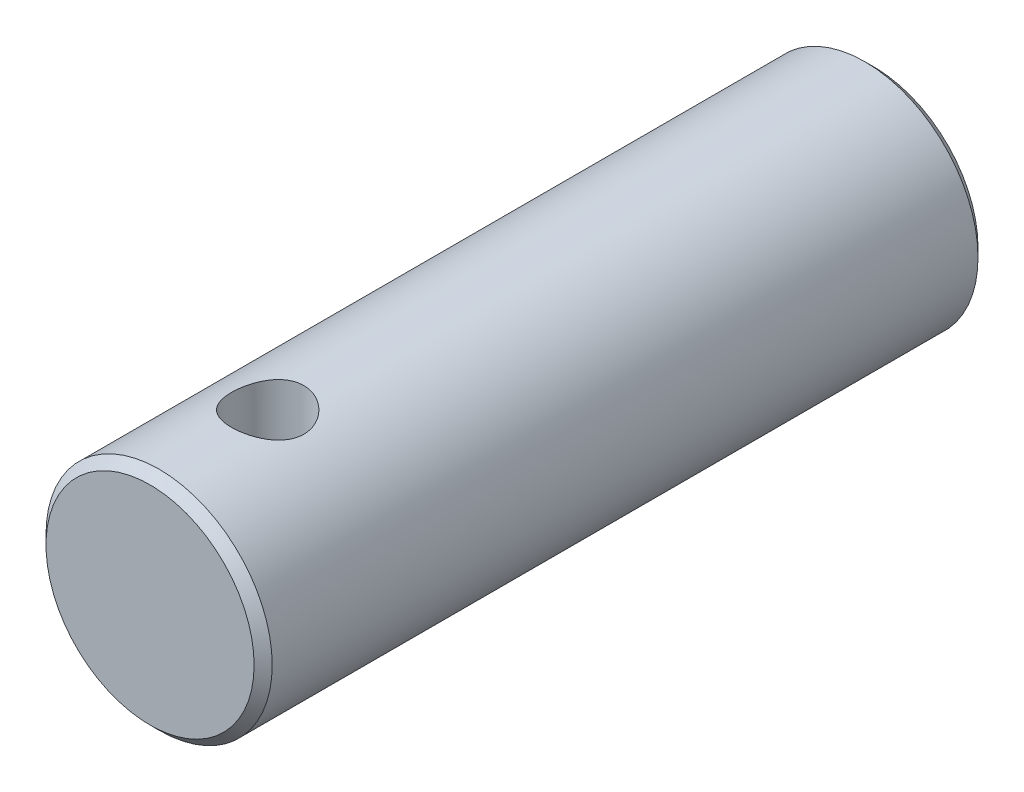
SolidWorks part; units mm, degrees
material "AISI 1020"
ref_plane "Front Plane" through (0, 0, 0) normal (0, 0, 1) x (1, 0, 0)
ref_plane "Top Plane" through (0, 0, 0) normal (0, 1, 0) x (1, 0, 0)
ref_plane "Right Plane" through (0, 0, 0) normal (1, 0, 0) x (0, 0, -1)
sketch "Sketch1" plane through (0, 0, 0) normal (0, 0, 1) x (1, 0, 0)
  line L0 (-22.5737, 0) -> (23.517, 0) construction
  line L1 (0, -18.5139) -> (0, 20.0975) construction
  circle A1 centre (0, 0) radius 12.5
  dimension "D1" = 25
extrude "Boss-Extrude4" add sketch "Sketch1" along normal blind 80
ref_plane "Plane2" through (0, 12.5, 0) normal (0, 1, 0) x (1, 0, 0)
sketch "Sketch5" plane through (0, 12.5, 0) normal (0, 1, 0) x (1, 0, 0)
  line L0 (0, 0) -> (0, -80) construction
  line L1 (-12.5, -80) -> (12.5, -80) construction
  circle A0 centre (0, -67) radius 4
  dimension "D1" = 8
  dimension "D2" = 67
extrude "Cut-Extrude4" cut sketch "Sketch5" against normal blind 8
chamfer "Chamfer5" distance 1 angle 45 2 edges at (12.5, 0, 0) (12.5, 0, 80)
